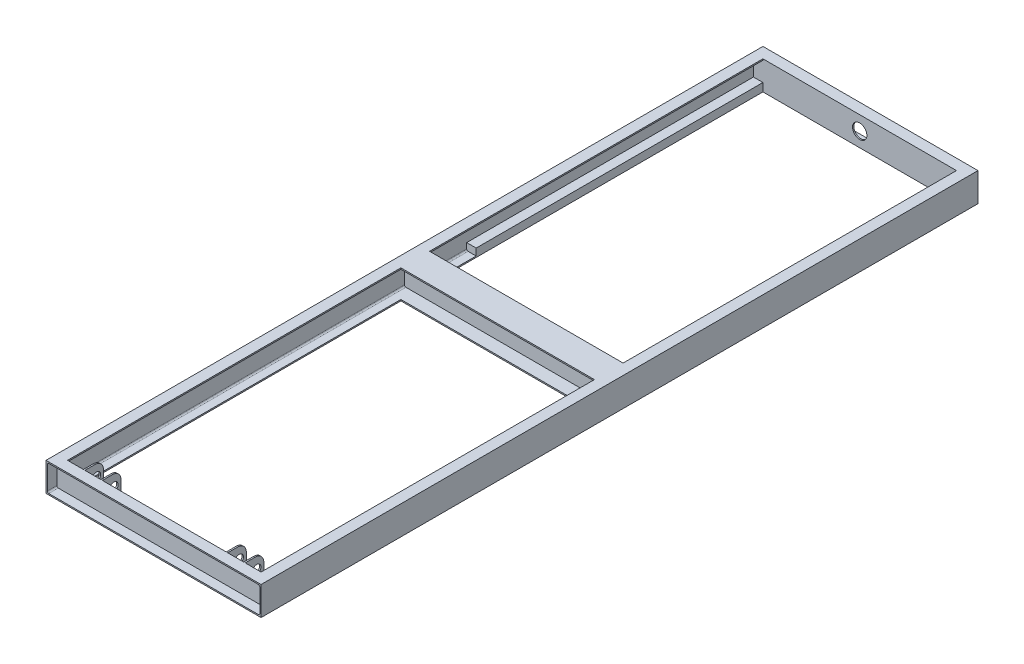
SolidWorks part; units mm, degrees
ref_plane "前视基准面" through (0, 0, 0) normal (0, 0, 1) x (1, 0, 0)
ref_plane "上视基准面" through (0, 0, 0) normal (0, 1, 0) x (1, 0, 0)
ref_plane "右视基准面" through (0, 0, 0) normal (1, 0, 0) x (0, 0, -1)
sketch "草图1" plane through (0, 0, 0) normal (0, 0, 1) x (1, 0, 0)
  line L0 (0, 40.3671) -> (0, -159.6329)
  line L1 (0, -159.6329) -> (75, -159.6329)
  line L2 (0, 40.3671) -> (75, 40.3671)
  line L3 (19, 31.3671) -> (75, 31.3671)
  line L4 (9, 21.3671) -> (9, -140.6329)
  line L5 (19, -150.6329) -> (75, -150.6329)
  line L6 (75, 40.3671) -> (75, 31.3671)
  line L7 (75, -150.6329) -> (75, -159.6329)
  line L8 (9, 31.3671) -> (9, -150.6329) construction
  line L9 (9, -150.6329) -> (75, -150.6329) construction
  line L10 (9, 31.3671) -> (75, 31.3671) construction
  arc A0 (9, -140.6329) -> (19, -150.6329) centre (19, -140.6329) ccw
  arc A1 (9, 21.3671) -> (19, 31.3671) centre (19, 21.3671) cw
  dimension "D2" = 10
  dimension "D1" = 9
extrude "凸台-拉伸1" add sketch "草图1" along normal blind 5000
sketch "草图2" plane through (0, 0, 0) normal (-1, 0, 0) x (0, 0, 1)
  line L0 (5000, 40.3671) -> (4925, 40.3671)
  line L1 (5000, 40.3671) -> (0, 40.3671) construction
  line L3 (4925, 40.3671) -> (4925, -159.6329)
  line L5 (5000, -159.6329) -> (0, -159.6329) construction
  line L6 (4925, -159.6329) -> (5000, -159.6329)
  line L7 (5000, 31.3671) -> (4934, 31.3671)
  line L8 (4934, 31.3671) -> (4934, -150.6329)
  line L9 (4934, -150.6329) -> (5000, -150.6329)
  line L10 (5000, 40.3671) -> (5000, 31.3671)
  line L11 (5000, -150.6329) -> (5000, -159.6329)
  line L13 (0, -150.6329) -> (0, -159.6329)
  line L14 (0, 40.3671) -> (0, 31.3671)
  line L15 (66, -150.6329) -> (0, -150.6329)
  line L16 (66, 31.3671) -> (66, -150.6329)
  line L17 (0, 31.3671) -> (66, 31.3671)
  line L18 (75, -159.6329) -> (0, -159.6329)
  line L19 (75, 40.3671) -> (75, -159.6329)
  line L20 (0, 40.3671) -> (75, 40.3671)
  dimension "D1" = 9
extrude "凸台-拉伸3" add sketch "草图2" against normal blind 1500
sketch "草图3" plane through (0, 0, 0) normal (0, 0, -1) x (-1, 0, 0)
  line L0 (-1500, 40.3671) -> (-1425, 40.3671)
  line L1 (-1500, 40.3671) -> (0, 40.3671) construction
  line L2 (-1500, 40.3671) -> (-1500, -159.6329)
  line L3 (-1500, -159.6329) -> (-1425, -159.6329)
  line L4 (0, -159.6329) -> (-1500, -159.6329) construction
  line L5 (-1481, -150.6329) -> (-1425, -150.6329)
  line L6 (-1491, 21.3671) -> (-1491, -140.6329)
  line L7 (-1481, 31.3671) -> (-1425, 31.3671)
  line L8 (-1425, 40.3671) -> (-1425, 31.3671)
  line L9 (-1425, -150.6329) -> (-1425, -159.6329)
  line L10 (-1491, 31.3671) -> (-1491, -150.6329) construction
  line L11 (-1491, -150.6329) -> (-1425, -150.6329) construction
  line L12 (-1491, 31.3671) -> (-1425, 31.3671) construction
  arc A0 (-1491, -140.6329) -> (-1481, -150.6329) centre (-1481, -140.6329) ccw
  arc A1 (-1491, 21.3671) -> (-1481, 31.3671) centre (-1481, 21.3671) cw
  dimension "D2" = 10
  dimension "D1" = 9
extrude "凸台-拉伸4" add sketch "草图3" against normal up to surface (5000 mm away)
sketch "草图5" plane through (0, 40.3671, 0) normal (0, 1, 0) x (1, 0, 0)
  line L0 (186, -4925) -> (186, -4795)
  line L4 (308, -4925) -> (308, -4795)
  line L5 (196, -4925) -> (196, -4795)
  line L6 (318, -4925) -> (318, -4795)
  line L7 (318, -4795) -> (308, -4795)
  line L8 (318, -4925) -> (308, -4925)
  line L9 (196, -4795) -> (186, -4795)
  line L10 (196, -4925) -> (186, -4925)
  line L14 (1304, -4925) -> (1314, -4925)
  line L15 (1304, -4795) -> (1314, -4795)
  line L16 (1182, -4925) -> (1192, -4925)
  line L17 (1182, -4795) -> (1192, -4795)
  line L18 (1182, -4925) -> (1182, -4795)
  line L19 (1304, -4925) -> (1304, -4795)
  line L20 (1192, -4925) -> (1192, -4795)
  line L21 (1314, -4925) -> (1314, -4795)
  dimension "D1" = 10
  dimension "D3" = 130
  dimension "D4" = 130
  dimension "D5" = 130
  dimension "D6" = 130
  dimension "D2" = 10
extrude "凸台-拉伸5" add sketch "草图5" against normal blind 200
sketch "草图6" plane through (318, 0, 0) normal (1, 0, 0) x (0, 0, -1)
  line L0 (-4795, -159.6329) -> (-4795, 40.3671) construction
  line L1 (-4925, 40.3671) -> (-4795, 40.3671) construction
  circle A0 centre (-4845, -39.6329) radius 30
  dimension "D1" = 50
  dimension "D2" = 80
extrude "切除-拉伸1" cut sketch "草图6" along normal blind 1006 and the other way blind 147
fillet "圆角1" radius 60 8 edges at (191, 40.3671, 4795) (191, -159.6329, 4795) (313, 40.3671, 4795) (313, -159.6329, 4795) (1187, 40.3671, 4795) (1187, -159.6329, 4795) (1309, 40.3671, 4795) (1309, -159.6329, 4795)
sketch "草图7" plane through (0, -150.6329, 0) normal (0, 1, 0) x (1, 0, 0)
  line L0 (75, -75) -> (75, -2075)
  line L1 (1425, -75) -> (1495, -75)
  line L2 (1425, -75) -> (1425, -2075)
  line L3 (1425, -2075) -> (1495, -2075)
  line L4 (1495, -75) -> (1495, -2075)
  line L5 (5, -75) -> (75, -75)
  line L6 (5, -2075) -> (75, -2075)
  line L7 (5, -75) -> (5, -2075)
  dimension "D1" = 70
  dimension "D2" = 2000
  dimension "D3" = 70
  dimension "D4" = 2000
extrude "凸台-拉伸6" add sketch "草图7" along normal blind 48
sketch "草图8" plane through (0, 0, 0) normal (-1, 0, 0) x (0, 0, 1)
  line L1 (5000, 40.3671) -> (0, 40.3671) construction
  line L2 (5000, -159.6329) -> (0, -159.6329) construction
  line L3 (2400, 40.3671) -> (2600, 40.3671)
  line L4 (2600, 40.3671) -> (2600, 31.3671)
  line L5 (2600, 31.3671) -> (2509, 31.3671)
  line L6 (2400, -159.6329) -> (2600, -159.6329)
  line L7 (2600, -159.6329) -> (2600, -150.6329)
  line L8 (2600, -150.6329) -> (2509, -150.6329)
  line L9 (2509, -150.6329) -> (2509, 31.3671)
  line L10 (2491, -150.6329) -> (2491, 31.3671)
  line L11 (2400, -150.6329) -> (2491, -150.6329)
  line L12 (2400, -159.6329) -> (2400, -150.6329)
  line L13 (2400, 31.3671) -> (2491, 31.3671)
  line L14 (2400, 40.3671) -> (2400, 31.3671)
extrude "凸台-拉伸7" add sketch "草图8" against normal up to surface (1491 mm away) up to face at (1491, -73.9662, 2358.3333)
sketch "草图9" plane through (0, 0, 66) normal (0, 0, -1) x (-1, 0, 0)
  circle A0 centre (-750, -59.6329) radius 50
  dimension "D1" = 100
extrude "切除-拉伸2" cut sketch "草图9" against normal blind 219
scale "缩放比例3" scale about origin uniform scaling yes scale factor 0.345
